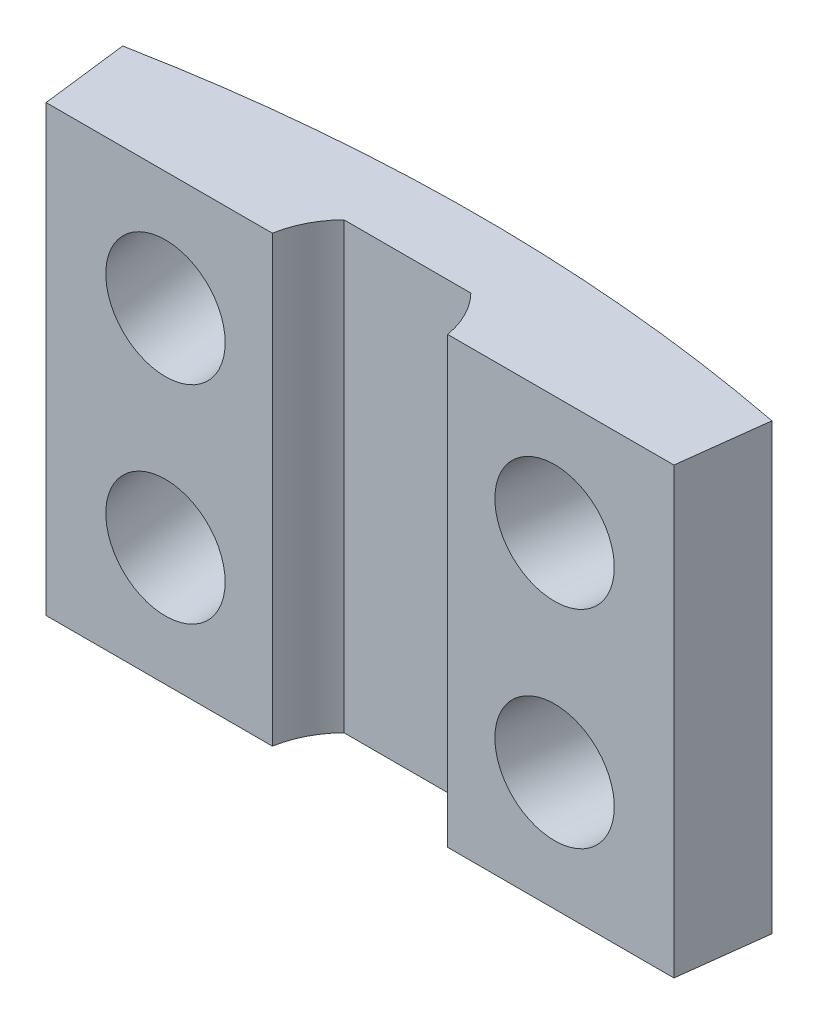
SolidWorks part; units mm, degrees
material "1023 碳钢板 (SS)"
ref_plane "前视基准面" through (0, 0, 0) normal (0, 0, 1) x (1, 0, 0)
ref_plane "上视基准面" through (0, 0, 0) normal (0, 1, 0) x (1, 0, 0)
ref_plane "右视基准面" through (0, 0, 0) normal (1, 0, 0) x (0, 0, -1)
sketch "草图1" plane through (0, 0, 0) normal (0, 1, 0) x (1, 0, 0)
  line L0 (0, 57.5) -> (0, 53) construction
  line L1 (-2.1424, 55.1) -> (2.1424, 55.1)
  line L3 (0, 53) -> (0, 0) construction
  line L4 (-10.599, 53.5) -> (-2.958, 53.5)
  line L5 (-10.9607, 56.4457) -> (-10.599, 53.5)
  line L6 (10.9607, 56.4457) -> (10.599, 53.5)
  line L7 (-8.9883, 56.7931) -> (-8.584, 53.5) construction
  line L8 (-5.0182, 57.2806) -> (-4.4926, 53) construction
  line L9 (0, 0) -> (-7.0075, 57.0714) construction
  line L10 (0, 53) -> (-10.9358, 53) construction
  line L11 (0, 0) -> (7.0075, 57.0714) construction
  line L12 (5.0182, 57.2806) -> (4.4926, 53) construction
  line L13 (8.9883, 56.7931) -> (8.584, 53.5) construction
  line L14 (0, 53) -> (13.3511, 53) construction
  line L15 (2.958, 53.5) -> (10.599, 53.5)
  circle A0 centre (0, 0) radius 57.5 construction
  arc A1 (-2.1424, 55.1) -> (-2.958, 53.5) centre (0, 53) ccw
  arc A2 (10.9607, 56.4457) -> (-10.9607, 56.4457) centre (0, 0) ccw
  arc A5 (2.958, 53.5) -> (2.1424, 55.1) centre (0, 53) ccw
  point P14 (0, 0)
  dimension "D1" = 115
  dimension "D3" = 6
  dimension "D7" = 0.5
  dimension "D10" = 14
  dimension "D8" = 57.5
  dimension "D4" = 3
  dimension "D2" = 4.5
  dimension "D5" = 4
  dimension "D6" = 2
  dimension "D9" = 2
  dimension "D11" = 2
  dimension "D12" = 0.5
  dimension "D13" = 4
  dimension "D14" = 2
  dimension "D15" = 97
  dimension "D16" = 2.1
  dimension "D17" = 97
extrude "凸台-拉伸1" add sketch "草图1" along normal blind 15
sketch3d "3D草图4" plane through (0, 0, 0) normal (0, 0, 1) x (1, 0, 0)
  dimension "D1" = 97
  dimension "D2" = 90
sketch "草图5" plane through (0, 0, 0) normal (-0.1219, 0, -0.9925) x (-0.9925, 0, 0.1219)
  line L0 (4, 15) -> (-17.758, 15) construction
  line L1 (-17.758, 0) -> (4, 0) construction
  line L2 (0, 50) -> (0, -50) construction
  circle A0 centre (0, 11) radius 2
  circle A1 centre (0, 4) radius 2
  dimension "D1" = 4
  dimension "D2" = 4
  dimension "D3" = 4
  dimension "D4" = 4
extrude "切除-拉伸6" cut sketch "草图5" along normal blind 85
sketch3d "3D草图5" plane through (0, 0, 0) normal (0, 0, 1) x (1, 0, 0)
  dimension "D1" = 263
  dimension "D2" = 270
sketch "草图6" plane through (0, 0, 0) normal (-0.1219, 0, 0.9925) x (0.9925, 0, 0.1219)
  line L0 (-3.584, 15) -> (4, 15) construction
  line L1 (-3.584, 0) -> (4, 0) construction
  line L2 (0, 50) -> (0, -50) construction
  circle A0 centre (0, 11) radius 2
  circle A1 centre (0, 4) radius 2
  dimension "D1" = 4
  dimension "D2" = 4
  dimension "D3" = 4
  dimension "D4" = 4
extrude "切除-拉伸7" cut sketch "草图6" against normal blind 85
